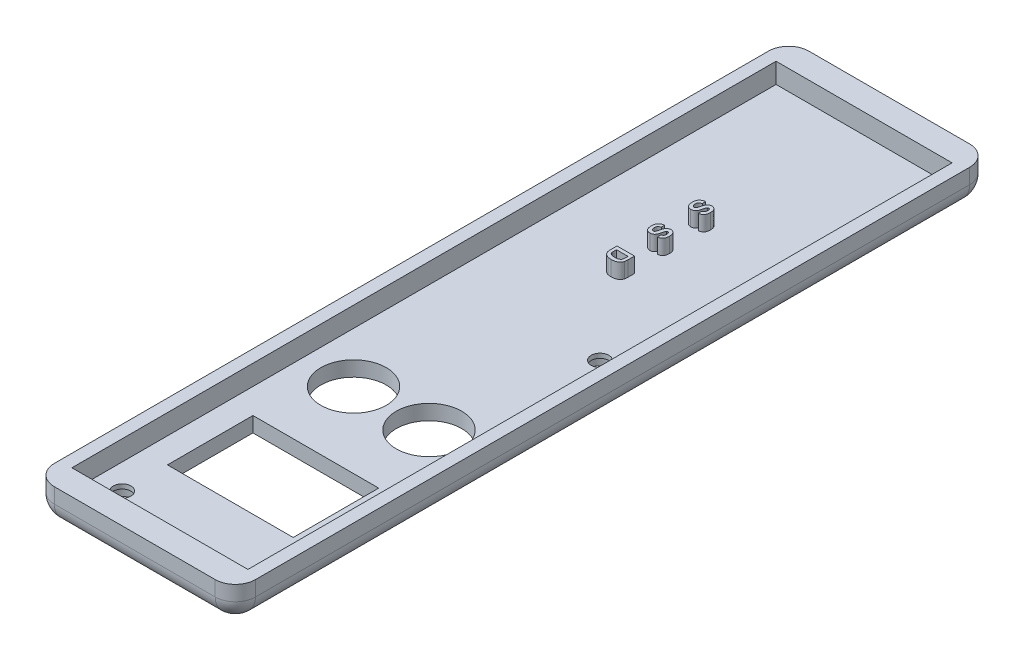
SolidWorks part; units mm, degrees
ref_plane "Front Plane" through (0, 0, 0) normal (0, 0, 1) x (1, 0, 0)
ref_plane "Top Plane" through (0, 0, 0) normal (0, 1, 0) x (1, 0, 0)
ref_plane "Right Plane" through (0, 0, 0) normal (1, 0, 0) x (0, 0, -1)
sketch "Sketch1" plane through (0, 0, 0) normal (0, 1, 0) x (1, 0, 0)
  line L1 (-20, -75) -> (20, -75)
  line L2 (-20, -75) -> (-20, 75)
  line L3 (-20, 75) -> (20, 75)
  line L4 (20, -75) -> (20, 75)
  line L5 (-20, -75) -> (20, 75) construction
  line L6 (-20, 75) -> (20, -75) construction
  point P0 (0, 0)
  dimension "D1" = 150
  dimension "D2" = 40
extrude "Boss-Extrude1" add sketch "Sketch1" along normal blind 3
sketch "Sketch2" plane through (0, 3, 0) normal (0, 1, 0) x (1, 0, 0)
  line L1 (-20, -75) -> (20, -75)
  line L2 (-20, -75) -> (-20, 75)
  line L3 (-20, 75) -> (20, 75)
  line L4 (20, -75) -> (20, 75)
  line L5 (-20, -75) -> (20, 75) construction
  line L6 (-20, 75) -> (20, -75) construction
  line L7 (-17.5, -70) -> (17.5, -70)
  line L8 (-17.5, -70) -> (-17.5, 70)
  line L9 (-17.5, 70) -> (17.5, 70)
  line L10 (17.5, -70) -> (17.5, 70)
  line L11 (-17.5, -70) -> (17.5, 70) construction
  line L12 (-17.5, 70) -> (17.5, -70) construction
  point P0 (0, 0)
  point P7 (0, 0)
  dimension "D1" = 140
  dimension "D2" = 35
extrude "Boss-Extrude2" add sketch "Sketch2" along normal blind 4
fillet "Fillet6" radius 4 8 edges at (0, 0, -75) (-20, 0, 0) (0, 0, 75) (20, 0, 0) (-20, 3.5, -75) (20, 3.5, -75) (20, 3.5, 75) (-20, 3.5, 75)
sketch "Sketch5" plane through (0, 0, 0) normal (0, -1, 0) x (1, 0, 0)
  line L1 (-12.5, 56) -> (12.5, 56)
  line L2 (-12.5, 56) -> (-12.5, 39)
  line L3 (-12.5, 39) -> (12.5, 39)
  line L4 (12.5, 56) -> (12.5, 39)
  line L48 (-20, -75) -> (-20, 75) construction
  line L49 (-20, 75) -> (20, 75) construction
  line L50 (20, 75) -> (20, -75) construction
  circle A0 centre (-7.5, 24) radius 6.5
  circle A1 centre (7.5, 24) radius 6.5
  point P14 (-20, 75)
  point P15 (20, 75)
  point P16 (-20, -75)
  point P17 (-20, 75)
  point P18 (20, -75)
  point P19 (-20, -75)
  point P20 (20, 75)
  point P21 (20, -75)
  point P22 (-20, 75)
  point P23 (20, 75)
  point P24 (-20, -75)
  point P25 (-20, 75)
  point P26 (20, -75)
  point P27 (-20, -75)
  point P28 (20, 75)
  point P29 (20, -75)
  point P30 (-17.5, 70)
  point P31 (17.5, 70)
  point P32 (-17.5, -70)
  point P33 (-17.5, 70)
  point P34 (17.5, -70)
  point P35 (-17.5, -70)
  point P36 (17.5, 70)
  point P37 (17.5, -70)
  point P38 (-17.5, 70)
  point P39 (17.5, 70)
  point P40 (-17.5, -70)
  point P41 (-17.5, 70)
  point P42 (17.5, -70)
  point P43 (-17.5, -70)
  point P44 (17.5, 70)
  point P45 (17.5, -70)
  point P46 (-20, 75)
  point P47 (20, 75)
  point P48 (-20, 75)
  point P49 (-20, -75)
  point P50 (-20, -75)
  point P51 (20, -75)
  point P52 (20, 75)
  point P53 (20, -75)
  point P54 (-20, 75)
  point P55 (20, -75)
  point P56 (-20, -75)
  point P57 (20, 75)
  point P58 (-20, 75)
  point P59 (20, 75)
  point P60 (-20, 75)
  point P61 (-20, -75)
  point P62 (-20, -75)
  point P63 (20, -75)
  point P64 (20, 75)
  point P65 (20, -75)
  point P66 (-20, 75)
  point P67 (20, -75)
  point P68 (-20, -75)
  point P69 (20, 75)
  point P70 (-17.5, 70)
  point P71 (17.5, 70)
  point P72 (-17.5, 70)
  point P73 (-17.5, -70)
  point P74 (-17.5, -70)
  point P75 (17.5, -70)
  point P76 (17.5, 70)
  point P77 (17.5, -70)
  point P78 (-17.5, 70)
  point P79 (17.5, -70)
  point P80 (-17.5, -70)
  point P81 (17.5, 70)
  point P82 (17.5, -70)
  point P83 (-17.5, -70)
  point P84 (-17.5, 70)
  point P85 (17.5, 70)
  point P86 (-17.5, -70)
  point P87 (-17.5, 70)
  point P88 (17.5, 70)
  point P89 (17.5, -70)
  point P90 (3.3, 0)
  point P91 (-3.3, 0)
  point P92 (0, -3.3)
  point P93 (0, 3.3)
  dimension "D1" = 13
  dimension "D2" = 13
  dimension "D3" = 7.5
  dimension "D4" = 19
  dimension "D5" = 25
  dimension "D6" = 17
  dimension "D7" = 12.5
  dimension "D8" = 12.5
  dimension "D9" = 15
  dimension "D10" = 15
extrude "Cut-Extrude1" cut sketch "Sketch5" against normal up to next
sketch "Sketch7" plane through (0, 0, 0) normal (0, -1, 0) x (1, 0, 0)
  line L5 (-20, 75) -> (20, 75) construction
  line L6 (-20, -75) -> (-20, 75) construction
  line L7 (20, -75) -> (-20, -75) construction
  line L8 (20, 75) -> (20, -75) construction
  circle A0 centre (-12.5, 65) radius 2.9
  circle A1 centre (12.5, -5) radius 2.9
  dimension "D1" = 5.8
  dimension "D2" = 5.8
  dimension "D3" = 70
  dimension "D4" = 7.5
  dimension "D5" = 10
  dimension "D6" = 7.5
extrude "Cut-Extrude7" cut sketch "Sketch7" against normal blind 2.1
sketch "Sketch8" plane through (0, 2.1, 0) normal (0, -1, 0) x (1, 0, 0)
  circle A0 centre (-12.5, 65) radius 1.75
  dimension "D1" = 3.5
extrude "Cut-Extrude8" cut sketch "Sketch8" against normal up to next
sketch "Sketch9" plane through (0, 2.1, 0) normal (0, -1, 0) x (1, 0, 0)
  circle A0 centre (12.5, -5) radius 1.75
  dimension "D1" = 3.5
extrude "Cut-Extrude9" cut sketch "Sketch9" against normal up to next
sketch "Sketch10" plane through (0, 3, 0) normal (0, 1, 0) x (1, 0, 0)
  line L0 (-17.5, 70) -> (-17.5, -70) construction
  line L1 (17.5, 70) -> (-17.5, 70) construction
  text T0 "<b><r-90>S</r></b>\r\n<b><r-90>S</r></b>\r\n<b><r-90>D</r></b>" font "Arial" height 3.5
  dimension "D1" = 15
  dimension "D2" = 30
extrude "Boss-Extrude3" add sketch "Sketch10" along normal blind 3
